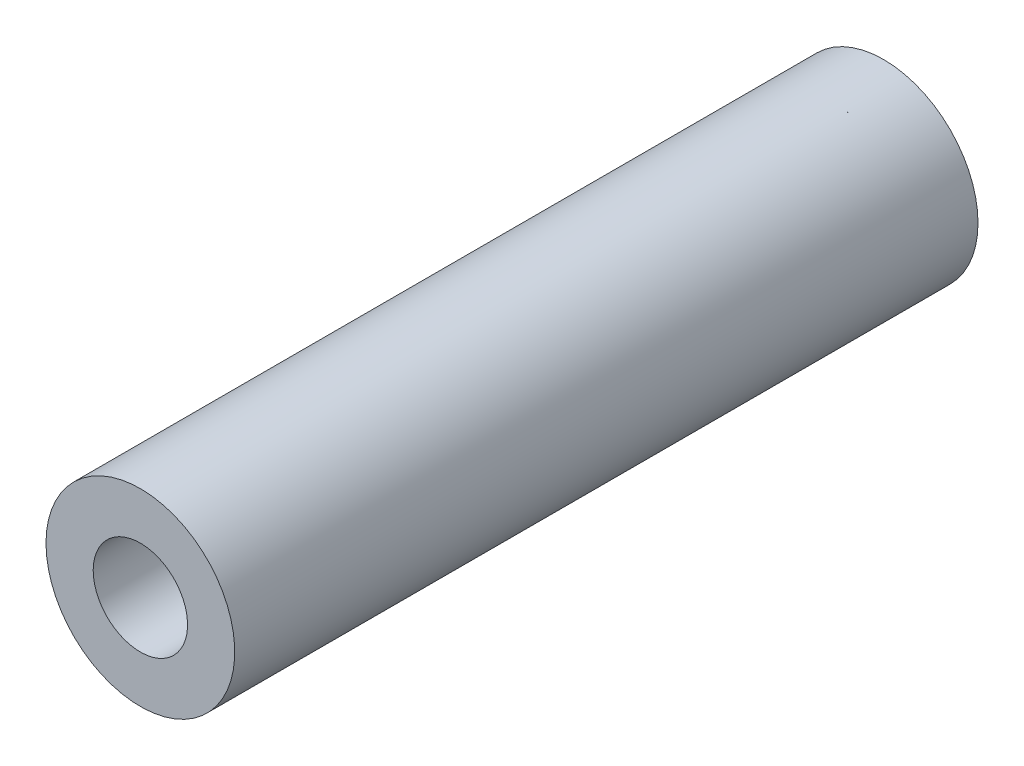
SolidWorks part; units mm, degrees
material "6061 Alloy"
ref_plane "Front Plane" through (0, 0, 0) normal (0, 0, 1) x (1, 0, 0)
ref_plane "Top Plane" through (0, 0, 0) normal (0, 1, 0) x (1, 0, 0)
ref_plane "Right Plane" through (0, 0, 0) normal (1, 0, 0) x (0, 0, -1)
sketch "Sketch1" plane through (0, 0, 0) normal (0, 0, 1) x (1, 0, 0)
  circle A0 centre (55.5752, -55.5752) radius 6.35
  circle A1 centre (55.5752, -55.5752) radius 3.175
  dimension "D1" = 12.7
  dimension "D2" = 6.35
extrude "Boss-Extrude1" add sketch "Sketch1" along normal up to surface (50.0126 mm away)
